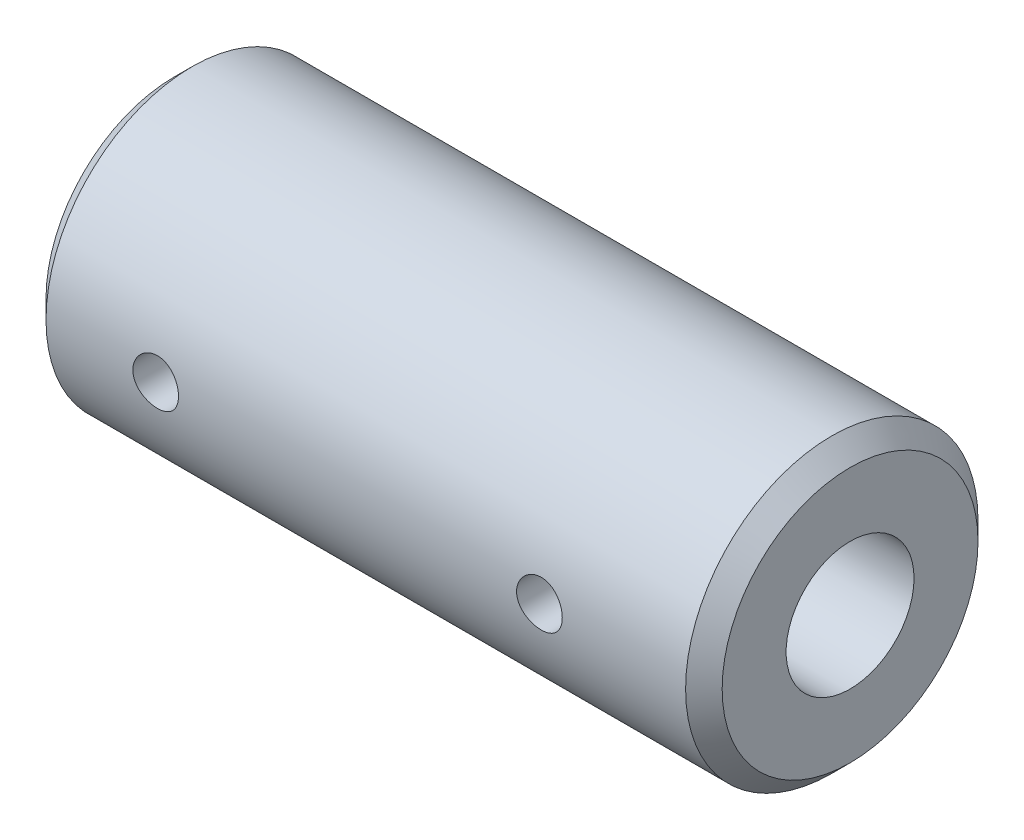
SolidWorks part; units mm, degrees
ref_plane "Front Plane" through (0, 0, 0) normal (0, 0, 1) x (1, 0, 0)
ref_plane "Top Plane" through (0, 0, 0) normal (0, 1, 0) x (1, 0, 0)
ref_plane "Right Plane" through (0, 0, 0) normal (1, 0, 0) x (0, 0, -1)
sketch "Sketch1" plane through (0, 0, 0) normal (0, 0, 1) x (1, 0, 0)
  line L0 (-18.5, 0) -> (18.5, 0) construction
  line L1 (-18.5, 0) -> (-18.5, 8)
  line L2 (-18.5, 8) -> (18.5, 8)
  line L3 (18.5, 8) -> (18.5, 0)
  line L4 (18.5, 0) -> (-18.5, 0)
  point P4 (0, 0)
  dimension "D1" = 16
  dimension "D2" = 37
revolve "Bloco" add sketch "Sketch1" angle 360 about L0
chamfer "Chanfros 1x45°" distance 1 angle 45 2 edges at (-18.5, -8, 0) (18.5, -8, 0)
hole_wizard "Furo M8x1.0 - Eixo Transmissão" positions "Sketch2" profile "Sketch3" tap size "M8x1.0" standard "ANSI Metric"
sketch "Sketch2" plane through (18.5, 0, 0) normal (1, 0, 0) x (0, 0, -1)
  point P0 (0, 0)
sketch "Sketch3" plane through (18.5, 0, 0) normal (0, 1, 0) x (0, 0, -1)
  line L0 (0, 0) -> (0, 17)
  line L1 (0, 17) -> (3.5, 14.897)
  line L2 (3.5, 14.897) -> (3.5, 0)
  line L5 (3.5, 0) -> (0, 0)
  line L10 (0, 17) -> (-3.5, 14.897) construction
  line L11 (0, -6.35) -> (0, 107.95) construction
  dimension "Tap Drill Dia." = 7
  dimension "Tap Drill Depth" = 17
  dimension "Drill Angle" = 118
cosmetic thread "Hole Thread1" parameters "D1"=16, "D2"=8
hole_wizard "Furo Ø5 - Eixo Motor" positions "Sketch4" profile "Sketch5" hole size "Ø5.0" standard "ANSI Metric"
sketch "Sketch4" plane through (-18.5, 0, 0) normal (-1, 0, 0) x (0, 0, 1)
  point P0 (0, 0)
sketch "Sketch5" plane through (-18.5, 0, 0) normal (0, 1, 0) x (0, 0, 1)
  line L0 (0, 0) -> (0, 16)
  line L1 (0, 16) -> (2.5, 14.4978)
  line L2 (2.5, 14.4978) -> (2.5, 0)
  line L5 (2.5, 0) -> (0, 0)
  line L10 (0, 16) -> (-2.5, 14.4978) construction
  line L11 (0, -6.35) -> (0, 107.95) construction
  dimension "Hole Dia." = 5
  dimension "Hole Depth" = 16
  dimension "Drill Angle" = 118
ref_plane "Plano de Referência" through (0, 0, 8) normal (0, 0, 1) x (1, 0, 0)
sketch "Posição Furos de Fixação" plane through (0, 0, 8) normal (0, 0, 1) x (1, 0, 0)
  line L0 (-18.5, 0) -> (18.5, 0) construction
  line L1 (-18.5, 7) -> (-18.5, -7) construction
  line L2 (18.5, -7) -> (18.5, 7) construction
  circle A0 centre (-11.5, 0) radius 1.5
  circle A1 centre (9.5, 0) radius 1.5
  dimension "D1" = 3
  dimension "D2" = 7
  dimension "D3" = 9
hole_wizard "Furos de Fixação M3x0.5" positions "Sketch7" profile "Sketch8" tap size "M3x0.5" standard "ANSI Metric"
sketch "Sketch7" plane through (0, 0, 8) normal (0, 0, 1) x (1, 0, 0)
  point P0 (9.5, 0)
  point P3 (-11.5, 0)
cosmetic thread "Hole Thread4" parameters "D2"=3
cosmetic thread "Hole Thread5" parameters "D2"=3
sketch "Sketch8" plane through (9.5, 0, 8) normal (1, 0, 0) x (0, -1, 0)
  line L0 (0, 0) -> (0, 4.5)
  line L1 (0, 4.5) -> (1.25, 4.5)
  line L2 (1.25, 4.5) -> (1.25, 0)
  line L5 (1.25, 0) -> (0, 0)
  line L11 (0, -6.35) -> (0, 107.95) construction
  dimension "Thru Tap Drill Dia." = 2.5
  dimension "Thru Tap Drill Depth" = 4.5
